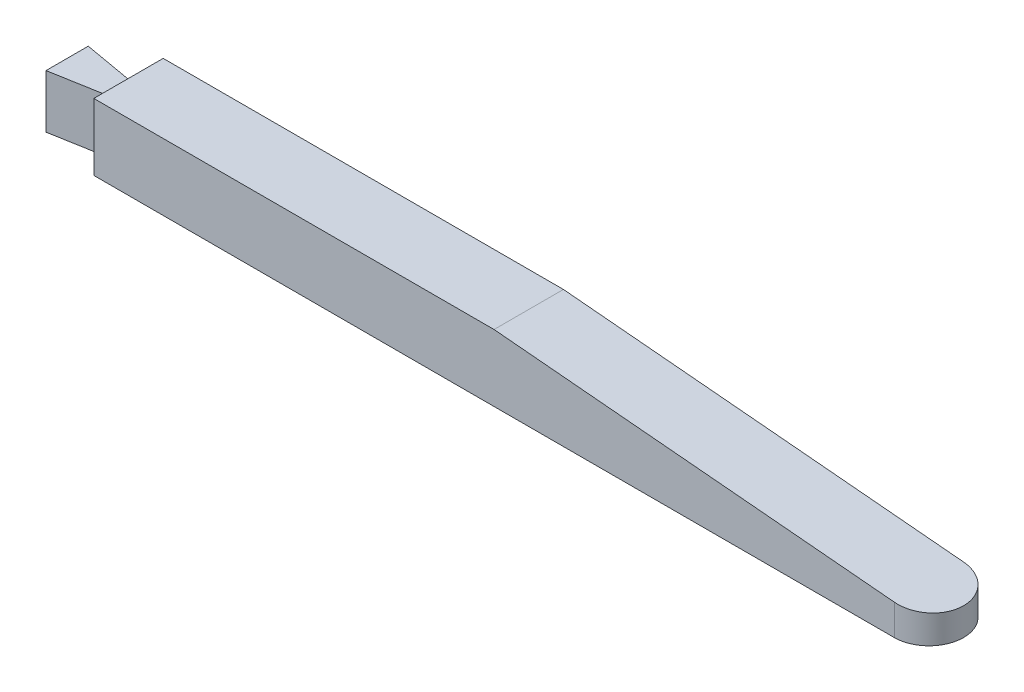
SolidWorks part; units mm, degrees
ref_plane "Front Plane" through (0, 0, 0) normal (0, 0, 1) x (1, 0, 0)
ref_plane "Top Plane" through (0, 0, 0) normal (0, 1, 0) x (1, 0, 0)
ref_plane "Right Plane" through (0, 0, 0) normal (1, 0, 0) x (0, 0, -1)
sketch "Sketch2" plane through (0, 0, 0) normal (0, 1, 0) x (1, 0, 0)
  line L10 (21.5028, -14.8255) -> (21.5028, -26.5943) construction
  line L29 (-13.5492, -8.6449) -> (-13.5492, -32.7749)
  line L30 (-13.5492, -8.6449) -> (21.5028, -14.8255)
  line L31 (-13.5492, -32.7749) -> (21.5028, -26.5943)
  line L32 (21.5028, -0.8979) -> (478.7028, -0.8979)
  line L33 (21.5028, -40.5219) -> (478.7028, -40.5219)
  line L35 (21.5028, -0.8979) -> (21.5028, -14.8255)
  line L36 (21.5028, -40.5219) -> (21.5028, -26.5943)
  line L37 (-13.5492, -20.7099) -> (21.5028, -20.7099) construction
  arc A3 (478.7028, -40.5219) -> (478.7028, -0.8979) centre (478.7028, -20.7099) ccw
  point P9 (0, 0)
  dimension "D4" = 80
  dimension "D5" = 39.624
  dimension "D8" = 39.624
  dimension "D3" = 80
  dimension "D2" = 24.13
  dimension "D6" = 457.2
  dimension "D7" = 457.2
  dimension "D9" = 13.5492
  dimension "D10" = 26.1183
  dimension "D11" = 13.9276
  dimension "D14" = 35.052
extrude "Boss-Extrude1" add sketch "Sketch2" along normal blind 38.1
sketch "Sketch3" plane through (0, 38.1, 0) normal (0, 1, 0) x (1, 0, 0)
  line L0 (-13.5492, -8.6449) -> (-13.5492, -32.7749)
  line L1 (-13.5492, -32.7749) -> (21.5028, -26.5943)
  line L2 (21.5028, -26.5943) -> (21.5028, -14.8255)
  line L3 (21.5028, -14.8255) -> (-13.5492, -8.6449)
extrude "Cut-Extrude1" cut sketch "Sketch3" against normal blind 7.62
sketch "Sketch5" plane through (0, 0, 40.5219) normal (0, 0, 1) x (1, 0, 0)
  line L0 (250.1028, 38.1) -> (498.5148, 15.7752)
  line L1 (21.5028, 38.1) -> (478.7028, 38.1) construction
  line L2 (498.5148, 0) -> (498.5148, 38.1) construction
  line L3 (498.5148, 15.7752) -> (498.5148, 38.1)
  line L4 (498.5148, 38.1) -> (250.1028, 38.1)
  dimension "D1" = 5.135
extrude "Cut-Extrude4" cut sketch "Sketch5" against normal blind 39.624
